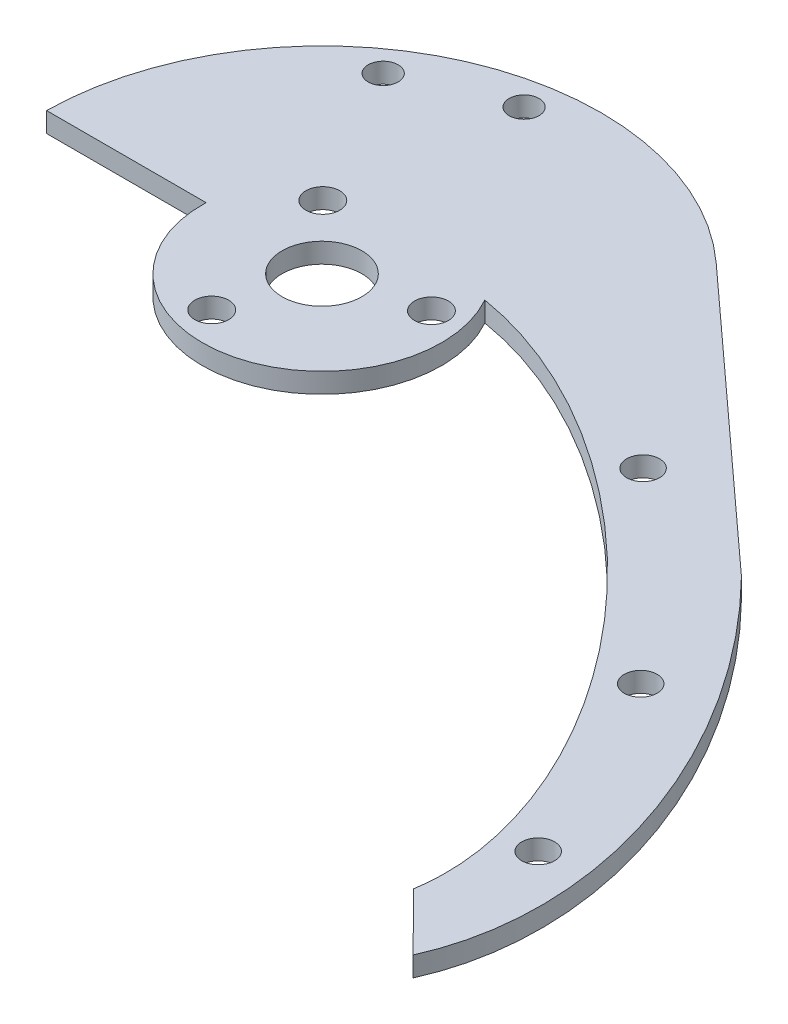
SolidWorks part; units mm, degrees
ref_plane "Спереди" through (0, 0, 0) normal (0, 0, 1) x (1, 0, 0)
ref_plane "Сверху" through (0, 0, 0) normal (0, 1, 0) x (1, 0, 0)
ref_plane "Справа" through (0, 0, 0) normal (1, 0, 0) x (0, 0, -1)
sketch "Эскиз1" plane through (0, 0, 0) normal (0, 1, 0) x (1, 0, 0)
  line L0 (-11.9945, 0.3627) -> (-27.9977, 0.3627)
  line L1 (0, 0) -> (51.9859, -52.6638) construction
  line L2 (-19.6703, 19.9268) -> (51.9859, -52.6638) construction
  line L3 (0, 0) -> (-9.6836, 9.8099) construction
  line L4 (47.3431, -5.2565) -> (18.858, 20.6973)
  line L5 (0, 0) -> (13.3374, 3.4813) construction
  line L6 (0, 0) -> (-4.7339, -17.2201) construction
  line L7 (25.9929, -26.3319) -> (58.7703, 6.0236) construction
  line L8 (58.0464, -48.8391) -> (63.7644, -54.6316)
  line L11 (0, 0) -> (51.9859, -52.6638) construction
  arc A0 (0, 28) -> (-27.9977, 0.3627) centre (0, 0) ccw
  arc A1 (0, 28) -> (18.858, 20.6973) centre (0, 0) cw
  circle A2 centre (0, 0) radius 9 construction
  circle A3 centre (0, 0) radius 10.7 construction
  circle A4 centre (-6.3226, 6.4051) radius 1.7
  circle A5 centre (0, 0) radius 4
  circle A6 centre (8.7082, 2.273) radius 1.7
  circle A7 centre (-2.3856, -8.6781) radius 1.7
  arc A8 (-11.9945, 0.3627) -> (10.4597, 5.8817) centre (0, 0) ccw
  ellipse E0 centre (25.9929, -26.3319) end of major axis (-7.7276, 7.8284) minor radius 30 (47.3431, -5.2565) -> (63.7644, -54.6316) cw
  ellipse E2 centre (25.9929, -26.3319) end of major axis (54.7959, -55.5104) minor radius 20.5 (58.0464, -48.8391) -> (10.4597, 5.8817) ccw
  dimension "D1" = 28
  dimension "D2" = 7
  dimension "D6" = 18
  dimension "D7" = 12
  dimension "D9" = 120
  dimension "D4" = 8
  dimension "D8" = 21.4
  dimension "D3" = 37
  dimension "D5" = 20.5
  dimension "D10" = 120
  dimension "D11" = 30
  dimension "D12" = 41
  dimension "D13" = 48
extrude "Бобышка-Вытянуть1" add sketch "Эскиз1" along normal blind 2
sketch "Эскиз2" plane through (0, 2, 0) normal (0, 1, 0) x (1, 0, 0)
  line L0 (0, 0) -> (0, 16.5609) construction
  line L1 (0, 0) -> (-2.989, 16.9517) construction
  line L2 (0, 0) -> (-6.9675, 16.8209) construction
  line L3 (0, 0) -> (51.9859, -52.6638) construction
  line L4 (25.9929, -26.3319) -> (37.778, 16.5379) construction
  line L5 (25.9929, -26.3319) -> (93.7048, -51.4749) construction
  line L6 (25.9929, -26.3319) -> (103.993, -5.9724) construction
  circle A0 centre (0, 0) radius 25 construction
  circle A1 centre (-4.3412, 24.6202) radius 1.5
  circle A2 centre (-14.3394, 20.4788) radius 1.5
  circle A3 centre (51.6199, -19.6428) radius 1.65
  circle A4 centre (61.0345, -39.3436) radius 1.65
  circle A5 centre (33.0135, -0.7937) radius 1.65
  ellipse E0 centre (25.9929, -26.3319) end of major axis (-5.6201, 5.6934) minor radius 24 construction
  dimension "D2" = 22.5
  dimension "D3" = 50
  dimension "D4" = 3
  dimension "D7" = 24
  dimension "D9" = 120
  dimension "D10" = 3.3
  dimension "D11" = 3.3
  dimension "D12" = 3.3
  dimension "D1" = 10
  dimension "D5" = 25
  dimension "D6" = 60
  dimension "D8" = 45
extrude "Вырез-Вытянуть2" cut sketch "Эскиз2" against normal through all
